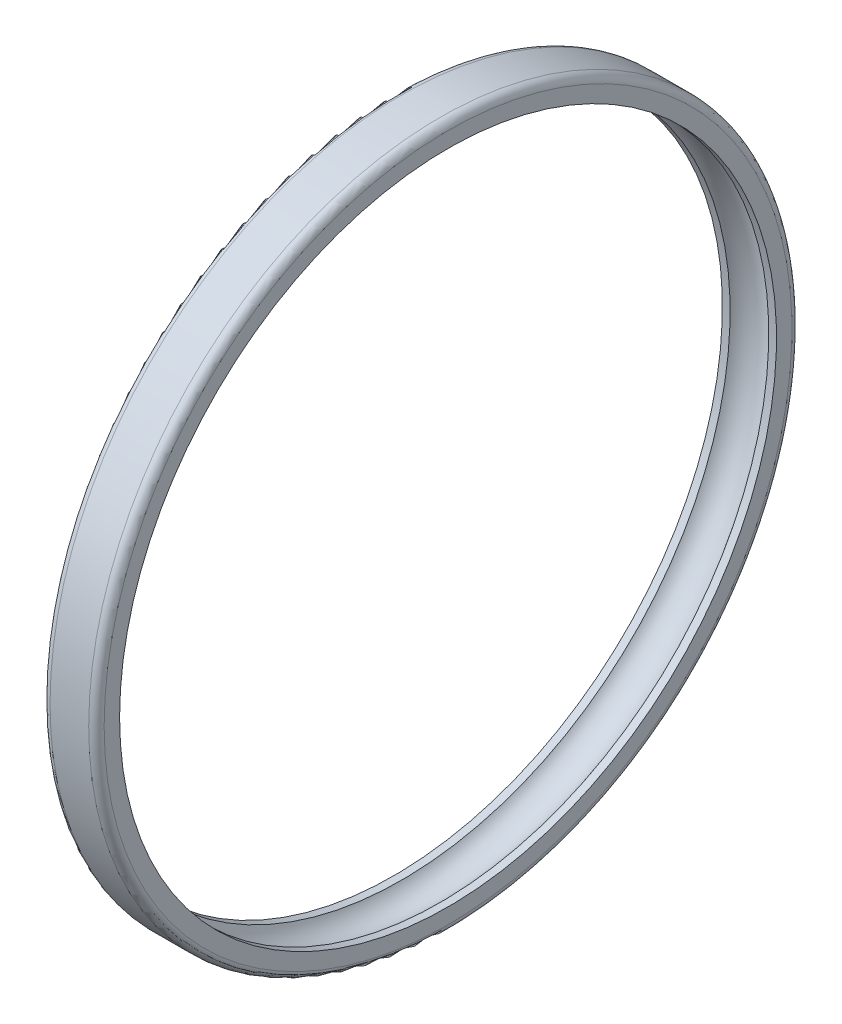
SolidWorks part; units mm, degrees
ref_plane "Front Plane" through (0, 0, 0) normal (0, 0, 1) x (1, 0, 0)
ref_plane "Top Plane" through (0, 0, 0) normal (0, 1, 0) x (1, 0, 0)
ref_plane "Right Plane" through (0, 0, 0) normal (1, 0, 0) x (0, 0, -1)
sketch "Sketch1" plane through (0, 0, 0) normal (0, 0, 1) x (1, 0, 0)
  line L0 (-592.7823, 0) -> (503.1421, 0) construction
  line L1 (31.75, 539.75) -> (44.45, 539.75)
  line L2 (-31.75, 577.85) -> (31.75, 577.85)
  line L3 (-44.45, 565.15) -> (-44.45, 539.75)
  line L4 (-44.45, 539.75) -> (-31.75, 539.75)
  line L5 (44.45, 565.15) -> (44.45, 539.75)
  line L6 (-44.45, 577.85) -> (44.45, 539.75) construction
  line L7 (-44.45, 539.75) -> (44.45, 577.85) construction
  arc A0 (31.75, 539.75) -> (-31.75, 539.75) centre (0, 518.6894) ccw
  arc A1 (31.75, 577.85) -> (44.45, 565.15) centre (31.75, 565.15) cw
  arc A2 (-31.75, 577.85) -> (-44.45, 565.15) centre (-31.75, 565.15) ccw
  point P3 (0, 558.8)
  point P9 (16.3185, 457.2)
  dimension "D4" = 38.1
  dimension "D5" = 12.7
  dimension "D6" = 12.7
  dimension "D1" = 1079.5
  dimension "D2" = 88.9
  dimension "D3" = 38.1
revolve "Revolve1" add sketch "Sketch1" angle 360 about L0
